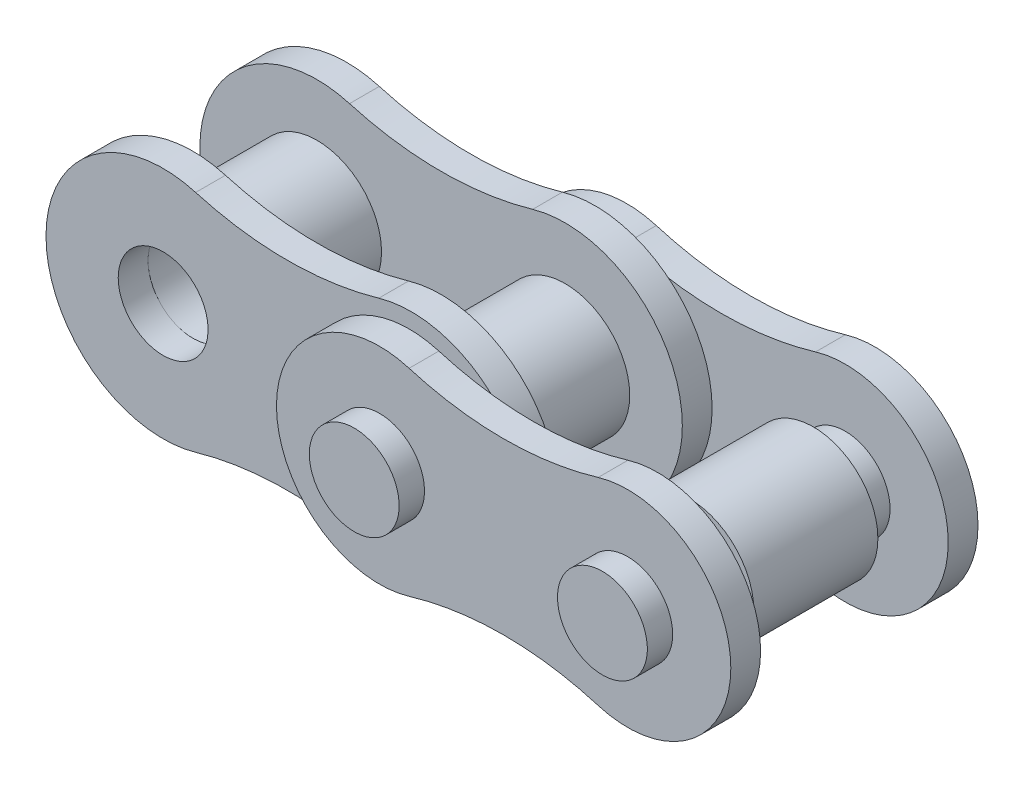
SolidWorks part; units mm, degrees
ref_plane "Front Plane" through (0, 0, 0) normal (0, 0, 1) x (1, 0, 0)
ref_plane "Top Plane" through (0, 0, 0) normal (0, 1, 0) x (1, 0, 0)
ref_plane "Right Plane" through (0, 0, 0) normal (1, 0, 0) x (0, 0, -1)
sketch "Sketch1" plane through (0, 0, 0) normal (0, 0, 1) x (1, 0, 0)
  line L0 (-3.175, 0) -> (3.175, 0) construction
  line L1 (-3.175, 2.9972) -> (-3.175, -2.9972) construction
  line L2 (0, -2.5476) -> (0, 2.5476) construction
  circle A0 centre (-3.175, 0) radius 1.651
  circle A1 centre (3.175, 0) radius 1.651
  circle A2 centre (-3.175, 0) radius 1.1493
  circle A3 centre (3.175, 0) radius 1.1493
  arc A4 (-2.3429, 2.8794) -> (-2.3429, -2.8794) centre (-3.175, 0) ccw
  arc A5 (2.3429, -2.8794) -> (2.3429, 2.8794) centre (3.175, 0) ccw
  arc A6 (-2.3429, 2.8794) -> (2.3429, 2.8794) centre (0, 10.9864) ccw
  arc A7 (-2.3429, -2.8794) -> (2.3429, -2.8794) centre (0, -10.9864) cw
  dimension "Roller Dia" = 3.302
  dimension "Pin Dia" = 2.2987
  dimension "Pitch" = 6.35
  dimension "H" = 5.9944
  dimension "D2" = 5.0952
sketch "Sketch2" plane through (0, 0, 0) normal (0, 1, 0) x (1, 0, 0)
  line L0 (0, 1.5875) -> (0, -1.5875) construction
  point P2 (0, -2.3495)
  point P4 (0, 2.3495)
  point P5 (0, 2.4003)
  point P6 (0, 3.1623)
  dimension "D1" = 0.762
  dimension "W" = 3.175
  dimension "T" = 0.762
  dimension "D2" = 0.762
  dimension "D3" = 0.0508
ref_plane "Plane1" through (0, 0, 1.5875) normal (0, 0, 1) x (1, 0, 0)
ref_plane "Plane2" through (0, 0, -2.4003) normal (0, 0, 1) x (1, 0, 0)
sketch "Sketch4" plane through (0, 0, 0) normal (0, 0, 1) x (1, 0, 0)
  circle A0 centre (-3.175, 0) radius 1.651 construction
  circle A1 centre (-3.175, 0) radius 1.651
  circle A2 centre (3.175, 0) radius 1.651 construction
  circle A3 centre (3.175, 0) radius 1.651
  circle A4 centre (-3.175, 0) radius 1.1747
  circle A5 centre (3.175, 0) radius 1.1747
  dimension "D1" = 2.3495
  dimension "D2" = 2.3495
extrude "Boss-Extrude1" add sketch "Sketch4" along normal mid plane 3.175
sketch "Sketch5" plane through (0, 0, 1.5875) normal (0, 0, 1) x (1, 0, 0)
  arc A0 (-2.3429, 2.8794) -> (-2.3429, -2.8794) centre (-3.175, 0) ccw construction
  arc A1 (-2.3429, 2.8794) -> (2.3429, 2.8794) centre (0, 10.9864) ccw construction
  circle A2 centre (-3.175, 0) radius 1.1493 construction
  arc A3 (2.3429, -2.8794) -> (2.3429, 2.8794) centre (3.175, 0) ccw construction
  circle A4 centre (3.175, 0) radius 1.1493 construction
  arc A5 (2.3429, -2.8794) -> (-2.3429, -2.8794) centre (0, -10.9864) ccw construction
  arc A6 (-2.3429, 2.8794) -> (-2.3429, -2.8794) centre (-3.175, 0) ccw
  arc A7 (-2.3429, 2.8794) -> (2.3429, 2.8794) centre (0, 10.9864) ccw
  circle A8 centre (-3.175, 0) radius 1.1493
  arc A9 (2.3429, -2.8794) -> (2.3429, 2.8794) centre (3.175, 0) ccw
  circle A10 centre (3.175, 0) radius 1.1493
  arc A11 (2.3429, -2.8794) -> (-2.3429, -2.8794) centre (0, -10.9864) ccw
extrude "Boss-Extrude2" add sketch "Sketch5" along normal up to vertex (0.762 mm away) separate body up to point (0, 0, 2.3495)
pattern_linear "LPattern1" count 2 spacing 6.35 along (1, 0, 0) of bodies 102
sketch "Sketch7" plane through (0, 0, -2.4003) normal (0, 0, 1) x (1, 0, 0)
  line L0 (9.525, 2.6375) -> (9.525, -2.6375) construction
  arc A0 (3.931, 2.5269) -> (3.931, -2.5269) centre (3.175, 0) ccw
  arc A1 (8.769, -2.5269) -> (8.769, 2.5269) centre (9.525, 0) ccw
  arc A2 (2.3429, -2.8794) -> (2.3429, 2.8794) centre (3.175, 0) ccw construction
  circle A3 centre (9.525, 0) radius 1.651 construction
  arc A4 (3.931, 2.5269) -> (8.769, 2.5269) centre (6.35, 10.6115) ccw
  arc A5 (3.931, -2.5269) -> (8.769, -2.5269) centre (6.35, -10.6115) cw
  arc A6 (-2.3429, 2.8794) -> (2.3429, 2.8794) centre (0, 10.9864) ccw construction
  circle A7 centre (3.175, 0) radius 1.1493 construction
  circle A8 centre (3.175, 0) radius 1.1493
  circle A9 centre (9.525, 0) radius 1.1493
  dimension "D2" = 5.2751
extrude "Boss-Extrude3" add sketch "Sketch7" against normal up to vertex (0.762 mm away) separate body up to point (0, 0, -3.1623)
mirror "Mirror1" about plane through (0, 0, 0) normal (0, 0, 1) of bodies 103 105
sketch "Sketch8" plane through (0, 0, 0) normal (0, 0, 1) x (1, 0, 0)
  circle A0 centre (3.175, 0) radius 1.1493
  circle A1 centre (9.525, 0) radius 1.1493
  circle A2 centre (3.175, 0) radius 1.1493 construction
  circle A3 centre (9.525, 0) radius 1.1494 construction
extrude "Boss-Extrude4" add sketch "Sketch8" against normal blind 3.81 and the other way blind 3.81 separate body
equation "\"D2@Sketch1\" =\"H@Sketch1\"*.85"
equation "\"D1@Sketch2\" = \"T@Sketch2\""
equation "\"D1@Sketch4\" = \"Pin Dia@Sketch1\"+.002"
equation "\"D2@Sketch4\" = \"D1@Sketch4\""
equation "\"D1@Boss-Extrude1\" = \"W@Sketch2\""
equation "\"D2@Sketch2\" = \"T@Sketch2\""
equation "\"D3@LPattern1\" = \"Pitch@Sketch1\""
equation "\"D3@LPattern2\" = \"Pitch@Sketch1\"*2"
equation "\"D2@Sketch7\" = \"H@Sketch1\"*.88"
